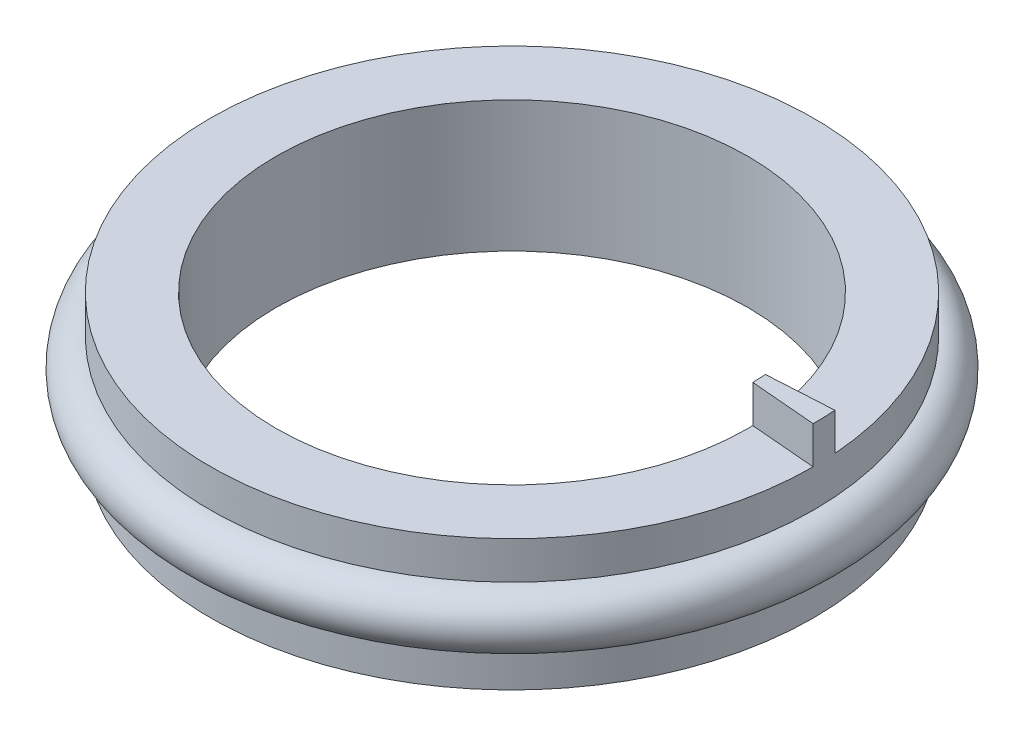
SolidWorks part; units mm, degrees
material "1023 Carbon Steel Sheet (SS)"
ref_plane "Front Plane" through (0, 0, 0) normal (0, 0, 1) x (1, 0, 0)
ref_plane "Top Plane" through (0, 0, 0) normal (0, 1, 0) x (1, 0, 0)
ref_plane "Right Plane" through (0, 0, 0) normal (1, 0, 0) x (0, 0, -1)
sketch "Sketch1" plane through (0, 0, 0) normal (0, 0, 1) x (1, 0, 0)
  line L0 (0, -133.9954) -> (0, 6565.7766) construction
  line L1 (8.06, -0.3526) -> (8.06, -1.3591)
  line L2 (6.3, 2.1409) -> (8.06, 2.1409)
  line L3 (6.3, 2.1409) -> (6.3, -1.3591)
  line L4 (6.3, -1.3591) -> (8.06, -1.3591)
  line L5 (8.06, 2.1409) -> (8.06, 1.1345)
  arc A0 (8.06, 1.1345) -> (8.06, -0.3526) centre (8.06, 0.3909) cw
  dimension "D1" = 12.6
  dimension "D2" = 16.12
  dimension "D3" = 3.5
revolve "Revolve1" add sketch "Sketch1" angle 360 about L0
sketch "Sketch2" plane through (0, 2.1409, 0) normal (0, 1, 0) x (1, 0, 0)
  line L0 (6.2986, 0.1336) -> (8.06, -0.0156)
  line L1 (6.2813, 0.485) -> (8.0387, 0.5859)
  arc A0 (6.2813, 0.485) -> (6.2986, 0.1336) centre (0, 0) cw
  circle A1 centre (0, 0) radius 6.3 construction
  arc A2 (8.0387, 0.5859) -> (8.06, -0.0156) centre (0, 0) cw
  circle A3 centre (0, 0) radius 8.06 construction
  point P10 (6.2878, 0.3913)
  point P11 (8.0387, 0.5859)
  point P12 (6.2986, 0.4863)
extrude "Boss-Extrude1" add sketch "Sketch2" along normal blind 1
